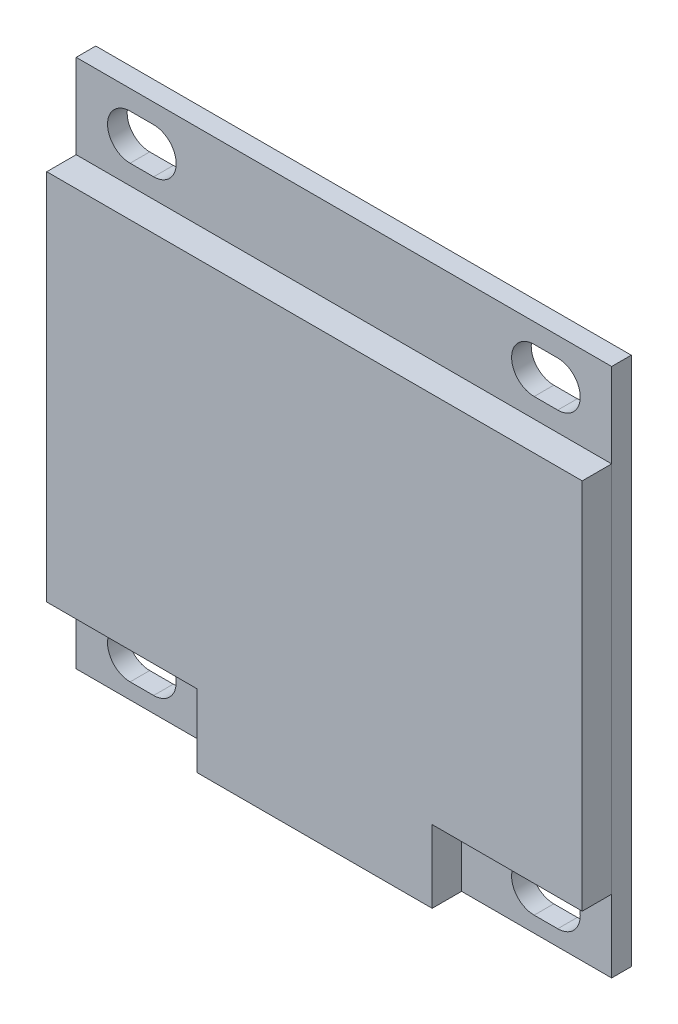
SolidWorks part; units mm, degrees
ref_plane "Front Plane" through (0, 0, 0) normal (0, 0, 1) x (1, 0, 0)
ref_plane "Top Plane" through (0, 0, 0) normal (0, 1, 0) x (1, 0, 0)
ref_plane "Right Plane" through (0, 0, 0) normal (1, 0, 0) x (0, 0, -1)
sketch "Sketch1" plane through (0, 0, 0) normal (0, 0, 1) x (1, 0, 0)
  line L1 (-13.65, -13.5) -> (13.65, -13.5)
  line L2 (-13.65, -13.5) -> (-13.65, 13.5)
  line L3 (-13.65, 13.5) -> (13.65, 13.5)
  line L4 (13.65, -13.5) -> (13.65, 13.5)
  line L5 (-13.65, -13.5) -> (13.65, 13.5) construction
  line L6 (-13.65, 13.5) -> (13.65, -13.5) construction
  point P0 (0, 0)
  dimension "D1" = 27
  dimension "D2" = 27.3
extrude "Boss-Extrude1" add sketch "Sketch1" along normal blind 1
sketch "Sketch2" plane through (0, 0, 1) normal (0, 0, 1) x (1, 0, 0)
  line L1 (-13.65, -9.8) -> (-6, -9.8)
  line L2 (-13.65, -9.8) -> (-13.65, 9.2)
  line L3 (-13.65, 9.2) -> (13.65, 9.2)
  line L4 (13.65, -9.8) -> (13.65, 9.2)
  line L6 (-13.65, 13.5) -> (-13.65, -13.5) construction
  line L7 (13.65, -13.5) -> (13.65, 13.5) construction
  line L8 (-13.65, -13.5) -> (13.65, -13.5) construction
  line L10 (-6, -9.8) -> (-6, -13.5)
  line L11 (-6, -13.5) -> (6, -13.5)
  line L12 (6, -13.5) -> (6, -9.8)
  line L13 (6, -9.8) -> (13.65, -9.8)
  dimension "D1" = 19
  dimension "D2" = 27.3
  dimension "D3" = 3.7
  dimension "D4" = 12
extrude "Boss-Extrude2" add sketch "Sketch2" along normal blind 1.5 separate body
sketch "Sketch3" plane through (0, 0, 1) normal (0, 0, 1) x (1, 0, 0)
  line L0 (-10.9, 11.35) -> (-9.7, 11.35) construction
  line L1 (-13.65, 13.5) -> (-13.65, -13.5) construction
  line L2 (-10.9, 12.5) -> (-9.7, 12.5)
  line L3 (-10.9, 10.2) -> (-9.7, 10.2)
  line L4 (13.65, 13.5) -> (-13.65, 13.5) construction
  line L7 (0, 0) -> (0, 50000) construction
  line L8 (10.9, 11.35) -> (9.7, 11.35) construction
  line L9 (10.9, 12.5) -> (9.7, 12.5)
  line L10 (10.9, 10.2) -> (9.7, 10.2)
  line L11 (-10.9, -11.55) -> (-9.7, -11.55) construction
  line L12 (-10.9, -10.4) -> (-9.7, -10.4)
  line L13 (-10.9, -12.7) -> (-9.7, -12.7)
  line L14 (10.9, -11.55) -> (9.7, -11.55) construction
  line L15 (10.9, -10.4) -> (9.7, -10.4)
  line L16 (10.9, -12.7) -> (9.7, -12.7)
  line L17 (-13.65, 13.5) -> (-13.65, -13.5) construction
  line L18 (-13.65, -13.5) -> (13.65, -13.5) construction
  arc A0 (-10.9, 12.5) -> (-10.9, 10.2) centre (-10.9, 11.35) ccw
  arc A1 (-9.7, 10.2) -> (-9.7, 12.5) centre (-9.7, 11.35) ccw
  arc A2 (10.9, 12.5) -> (10.9, 10.2) centre (10.9, 11.35) cw
  arc A3 (9.7, 10.2) -> (9.7, 12.5) centre (9.7, 11.35) cw
  arc A4 (-10.9, -10.4) -> (-10.9, -12.7) centre (-10.9, -11.55) ccw
  arc A5 (-9.7, -12.7) -> (-9.7, -10.4) centre (-9.7, -11.55) ccw
  arc A6 (10.9, -10.4) -> (10.9, -12.7) centre (10.9, -11.55) cw
  arc A7 (9.7, -12.7) -> (9.7, -10.4) centre (9.7, -11.55) cw
  point P2 (-12.05, 11.35)
  point P3 (-8.55, 11.35)
  point P4 (-10.3, 11.35)
  point P18 (0, 13.5)
  point P19 (10.3, 11.35)
  point P26 (-10.3, -11.55)
  point P31 (-12.05, -11.55)
  point P32 (-8.55, -11.55)
  point P35 (10.3, -11.55)
  dimension "D1" = 3.5
  dimension "D2" = 2.3
  dimension "D3" = 1.6
  dimension "D4" = 1
  dimension "D5" = 2.3
  dimension "D6" = 3.5
  dimension "D7" = 1.6
  dimension "D8" = 0.8
extrude "Cut-Extrude1" cut sketch "Sketch3" against normal through all
